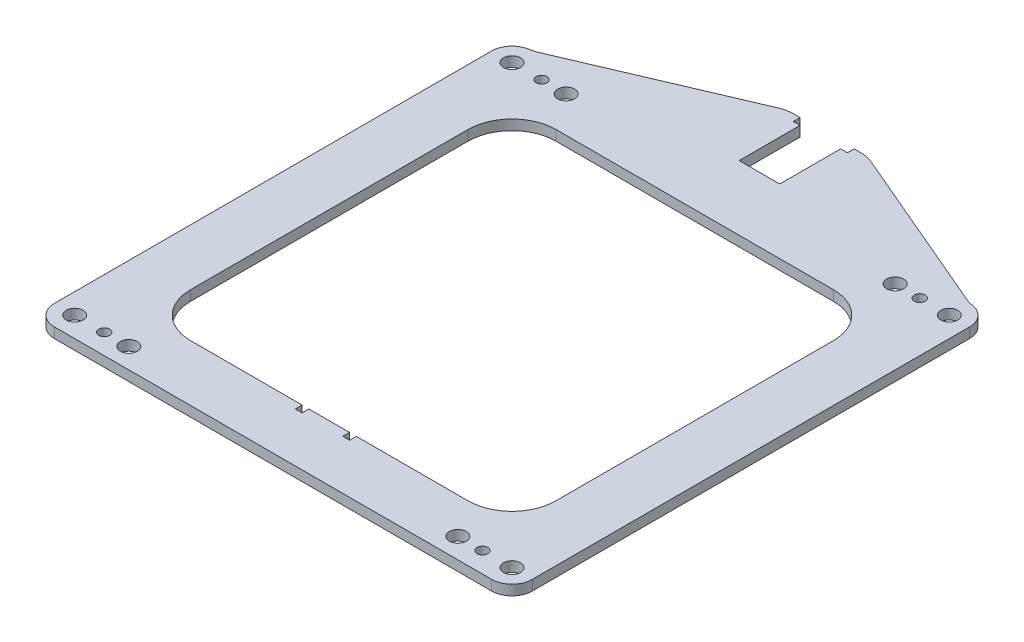
SolidWorks part; units mm, degrees
ref_plane "Front Plane" through (0, 0, 0) normal (0, 0, 1) x (1, 0, 0)
ref_plane "Top Plane" through (0, 0, 0) normal (0, 1, 0) x (1, 0, 0)
ref_plane "Right Plane" through (0, 0, 0) normal (1, 0, 0) x (0, 0, -1)
sketch "Sketch1" plane through (0, 0, 0) normal (0, 1, 0) x (1, 0, 0)
  point P0 (0, 54)
  point P1 (-54, 0)
  line B0 (41, 54) -> (-41, 54)
  line B1 (9.8546, 93.1) -> (6, 93.1)
  line B2 (-13.7811, 92.2969) -> (-63.1825, 71.2052)
  line B3 (-70.6, 64.6) -> (-70.6, -64.6)
  arc B4 (-70.6, -64.6) -> (-64.6, -70.6) centre (-64.6, -64.6) ccw
  line B5 (-64.6, -70.6) -> (64.6, -70.6)
  arc B6 (64.6, -70.6) -> (70.6, -64.6) centre (64.6, -64.6) ccw
  line B7 (70.6, -64.6) -> (70.6, 64.6)
  arc B8 (70.6, 64.6) -> (65.5409, 70.5258) centre (64.6, 64.6) ccw
  arc B9 (63.1825, 71.2052) -> (65.5409, 70.5258) centre (67.1091, 80.402) ccw
  line B10 (63.1825, 71.2052) -> (13.7811, 92.2969)
  arc B11 (13.7811, 92.2969) -> (9.8546, 93.1) centre (9.8546, 83.1) ccw
  arc B12 (-9.8546, 93.1) -> (-13.7811, 92.2969) centre (-9.8546, 83.1) ccw
  arc B13 (-65.5409, 70.5258) -> (-63.1825, 71.2052) centre (-67.1091, 80.402) ccw
  arc B14 (-65.5409, 70.5258) -> (-70.6, 64.6) centre (-64.6, 64.6) ccw
  line B15 (-6, 73.1) -> (-6, 93.1)
  line B16 (6, 73.1) -> (6, 93.1)
  line B17 (6, 73.1) -> (-6, 73.1)
  line B18 (-41, -54) -> (41, -54)
  line B19 (54, -41) -> (54, 41)
  line B20 (-54, 41) -> (-54, -41)
  line B21 (-6, 93.1) -> (-9.8546, 93.1)
  circle B22 centre (64.6, -64.6) radius 2.5
  circle B23 centre (48.6, -64.6) radius 2.5
  circle B24 centre (-55.87, 64.6) radius 1.6
  circle B25 centre (55.87, -64.6) radius 1.6
  circle B26 centre (-48.6, 64.6) radius 2.5
  circle B27 centre (55.87, 64.6) radius 1.6
  circle B28 centre (48.6, 64.6) radius 2.5
  circle B29 centre (64.6, 64.6) radius 2.5
  circle B30 centre (-55.87, -64.6) radius 1.6
  circle B31 centre (-48.6, -64.6) radius 2.5
  circle B32 centre (-64.6, -64.6) radius 2.5
  circle B33 centre (-64.6, 64.6) radius 2.5
  circle B34 centre (48.6, 64.6) radius 2.5
  circle B35 centre (64.6, 64.6) radius 2.5
  circle B36 centre (-48.6, -64.6) radius 2.5
  circle B37 centre (-64.6, -64.6) radius 2.5
  arc B38 (-54, -41) -> (-41, -54) centre (-41, -41) ccw
  arc B39 (41, -54) -> (54, -41) centre (41, -41) ccw
  arc B40 (54, 41) -> (41, 54) centre (41, 41) ccw
  arc B41 (-41, 54) -> (-54, 41) centre (-41, 41) ccw
sketch_block_instance "Layer1-1"
sketch_block "Layer1"
extrude "Boss-Extrude1" add sketch "Sketch1" along normal blind 3 contours B5 B6 B7 B8 B9 B10 B11 B1 B16 B17 B15 B21 B12 B2 B13 B14 B3 B4 B41 B0 B40 B19 B39 B18 B38 B20 B22 B23 B24 B25 B26 B27 B28 B29 B30 B31 B32 B33
sketch "Sketch2" plane through (0, 3, 0) normal (0, 1, 0) x (1, 0, 0)
  line L0 (-41, -54) -> (41, -54) construction
  line L1 (-6, 93.1) -> (-8, 93.1)
  line L2 (-6, 93.1) -> (-6, 91.1)
  line L3 (-6, 91.1) -> (-8, 91.1)
  line L4 (-8, 93.1) -> (-8, 91.1)
  line L5 (6, 93.1) -> (8, 93.1)
  line L6 (6, 93.1) -> (6, 91.1)
  line L7 (6, 91.1) -> (8, 91.1)
  line L8 (8, 93.1) -> (8, 91.1)
  line L9 (-8, -54) -> (-6, -54)
  line L10 (-8, -54) -> (-8, -56)
  line L11 (-8, -56) -> (-6, -56)
  line L12 (8, -54) -> (8, -56)
  line L14 (-6, -54) -> (-6, -56)
  line L16 (6, -54) -> (8, -54)
  line L17 (6, -56) -> (8, -56)
  line L18 (6, -56) -> (6, -54)
  dimension "D1" = 2
extrude "Cut-Extrude1" cut sketch "Sketch2" against normal through all
